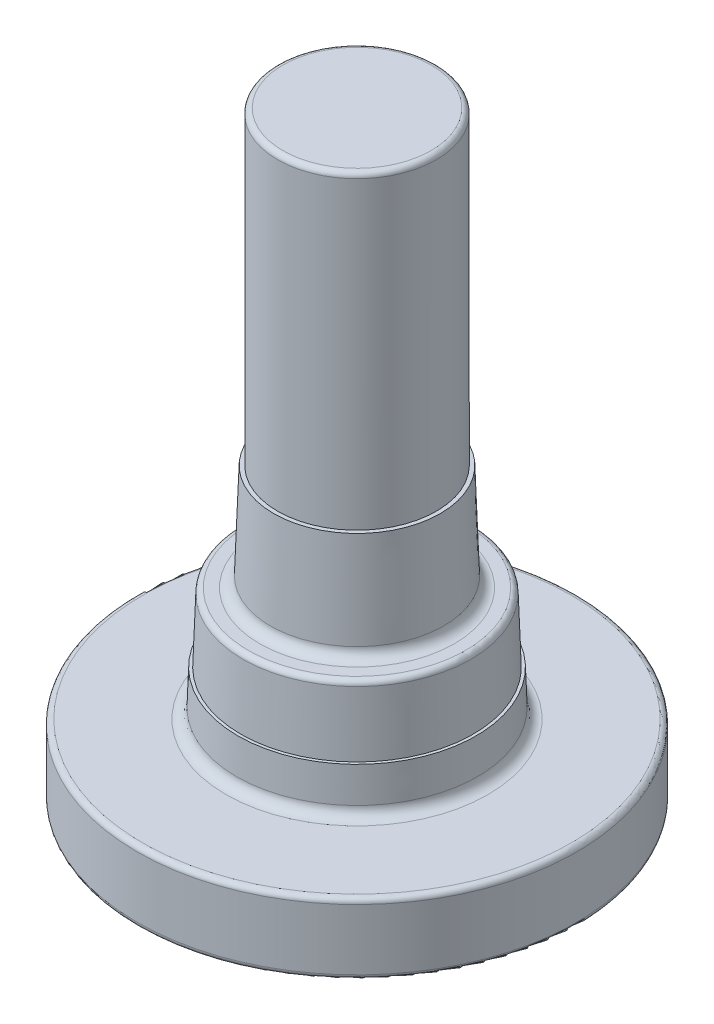
SolidWorks part; units mm, degrees
ref_plane "Plano frontal" through (0, 0, 0) normal (0, 0, 1) x (1, 0, 0)
ref_plane "Plano superior" through (0, 0, 0) normal (0, 1, 0) x (1, 0, 0)
ref_plane "Plano direito" through (0, 0, 0) normal (1, 0, 0) x (0, 0, -1)
sketch "Esboço1" plane through (0, 0, 0) normal (0, 0, 1) x (1, 0, 0)
  line L0 (0, 75.2133) -> (0, -58.1685) construction
  line L1 (0, -34.7867) -> (20, -34.7867)
  line L2 (20, -34.7867) -> (20.1222, -38.2867)
  line L3 (20.1222, -38.2867) -> (41.5, -38.2867)
  line L4 (41.5, -38.2867) -> (41.5, -24.7867)
  line L5 (41.5, -24.7867) -> (22.7968, -24.7867)
  line L6 (22.7968, -24.7867) -> (22.5, -16.2867)
  line L7 (22.5, -16.2867) -> (21.954, -16.2867)
  line L8 (21.954, -16.2867) -> (21.5, -3.2867)
  line L9 (21.5, -3.2867) -> (16.4484, -3.2867)
  line L10 (16.4484, -3.2867) -> (15.75, 16.7133)
  line L11 (15.75, 16.7133) -> (15, 16.7133)
  line L12 (15, 16.7133) -> (15, 75.2133)
  line L13 (15, 75.2133) -> (0, 75.2133)
  line L14 (0, 75.2133) -> (0, -34.7867)
  dimension "D2" = 20
  dimension "D3" = 2
  dimension "D4" = 22.5
  dimension "D5" = 2
  dimension "D6" = 21.5
  dimension "D7" = 2
  dimension "D8" = 15.75
  dimension "D9" = 15
  dimension "D10" = 3.5
  dimension "D11" = 41.5
  dimension "D12" = 22
  dimension "D13" = 13.5
  dimension "D14" = 35
  dimension "D15" = 55
  dimension "D16" = 113.5
revolve "Revolução1" add sketch "Esboço1" angle 360 about L0
fillet "Filete1" radius 2 1 edges at (0, -24.7867, 22.7968)
fillet "Filete2" radius 2 1 edges at (0, -3.2867, 16.4484)
fillet "Filete3" radius 1 4 edges at (0, 75.2133, 15) (0, -3.2867, 21.5) (0, -38.2867, 41.5) (0, -24.7867, 41.5)
fillet "Filete4" radius 1 2 edges at (0, -38.2867, 20.1222) (0, -34.7867, 20)
sketch "Esboço2" plane through (0, -34.7867, 0) normal (0, -1, 0) x (1, 0, 0)
  line L0 (-41.5, 0) -> (41.5, 0) construction
  line L2 (-7.5, 12.5) -> (7.5, 12.5)
  line L3 (-7.5, 12.5) -> (-7.5, -15.5)
  line L4 (-7.5, -15.5) -> (7.5, -15.5)
  line L5 (7.5, 12.5) -> (7.5, -15.5)
  line L6 (-7.5, 12.5) -> (7.5, -15.5) construction
  line L7 (-7.5, -15.5) -> (7.5, 12.5) construction
  circle A0 centre (0, 0) radius 41.5 construction
  point P5 (0, -1.5)
  dimension "D1" = 15
  dimension "D2" = 28
extrude "Corte-extrusão1" cut sketch "Esboço2" against normal blind 7
fillet "Filete6" radius 0.5 12 edges at (0, -34.7867, 12.5) (-7.5, -31.2867, 12.5) (7.5, -31.2867, 12.5) (7.5, -31.2867, -15.5) (-7.5, -31.2867, -15.5) (0, -27.7867, 12.5) (7.5, -27.7867, -1.5) (0, -27.7867, -15.5) (-7.5, -27.7867, -1.5) (7.5, -34.7867, -1.5) (0, -34.7867, -15.5) (-7.5, -34.7867, -1.5)
